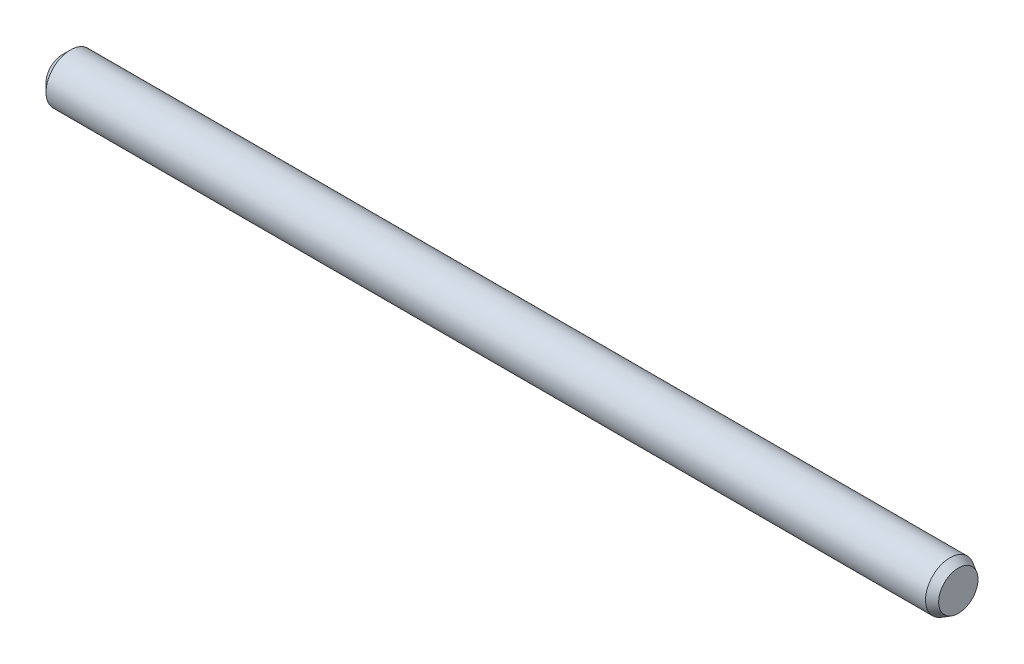
SolidWorks part; units mm, degrees
ref_plane "Alzado" through (0, 0, 0) normal (0, 0, 1) x (1, 0, 0)
ref_plane "Planta" through (0, 0, 0) normal (0, 1, 0) x (1, 0, 0)
ref_plane "Vista lateral" through (0, 0, 0) normal (1, 0, 0) x (0, 0, -1)
sketch "Croquis1" plane through (0, 0, 0) normal (1, 0, 0) x (0, 0, -1)
  circle A0 centre (0, 0) radius 1.475
  dimension "D1" = 2.95
extrude "Saliente-Extruir1" add sketch "Croquis1" along normal blind 54
chamfer "Chaflán1" distance 0.5 angle 30 1 edges at (54, 0, -1.475)
chamfer "Chaflán2" distance 0.5 angle 45 1 edges at (0, 0, -1.475)
